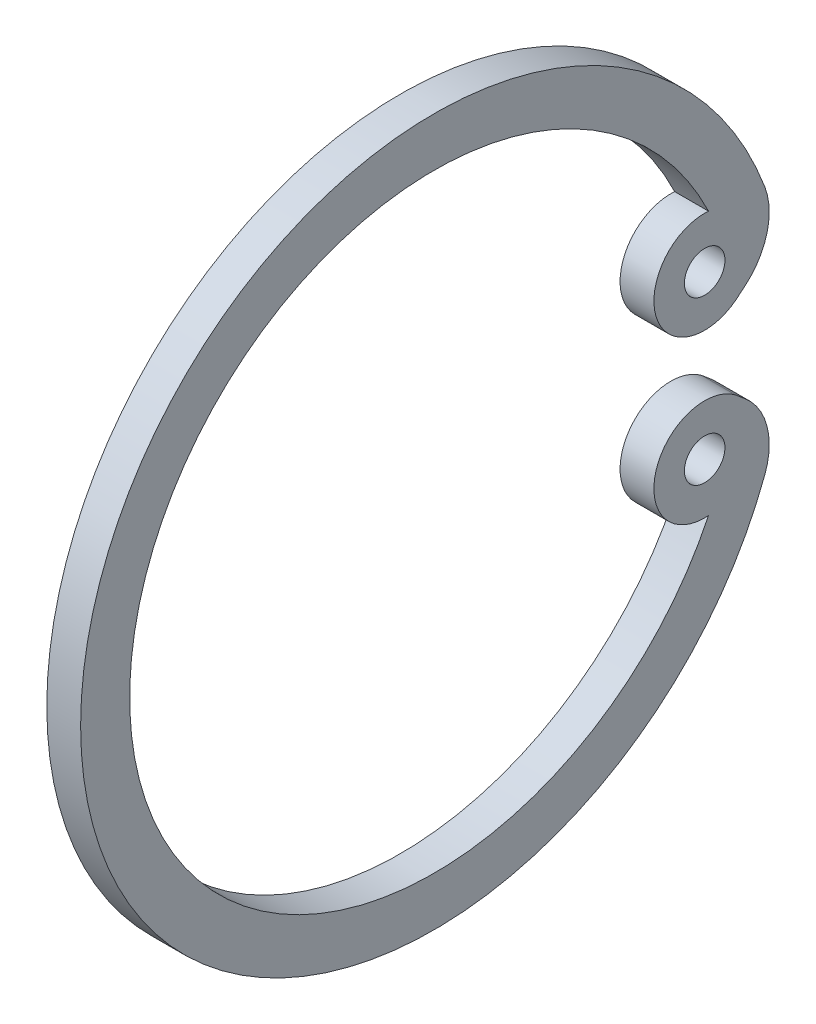
SolidWorks part; units mm, degrees
ref_plane "Front Plane" through (0, 0, 0) normal (0, 0, 1) x (1, 0, 0)
ref_plane "Top Plane" through (0, 0, 0) normal (0, 1, 0) x (1, 0, 0)
ref_plane "Right Plane" through (0, 0, 0) normal (1, 0, 0) x (0, 0, -1)
ref_plane "Plane1" through (19, 0, 0) normal (1, 0, 0) x (0, 0, -1)
sketch "Sketch1" plane through (19, 0, 0) normal (1, 0, 0) x (0, 0, -1)
  line L0 (-1.0829, 1.2142) -> (-0.8063, 1.4448)
  line L1 (-0.8063, -1.4451) -> (-1.0822, -1.2136)
  arc A0 (-1.8869, 3.8965) -> (-1.0829, 1.2142) centre (-2.0005, 2.4008) ccw
  arc A1 (-0.8063, 1.4448) -> (-0.2201, 3.6816) centre (-2.0918, 2.9769) ccw
  arc A2 (-0.2201, 3.6816) -> (-0.2201, -3.6818) centre (-9.9996, -0.0001) ccw
  arc A3 (-0.2201, -3.6818) -> (-0.8063, -1.4451) centre (-2.0918, -2.9772) ccw
  arc A4 (-1.0822, -1.2136) -> (-1.8869, -3.8967) centre (-2.0004, -2.4004) ccw
  arc A5 (-1.8869, -3.8967) -> (-1.8869, 3.8965) centre (-9.9996, -0.0001) cw
  circle A6 centre (-2, -2.4) radius 0.6
  circle A7 centre (-2, 2.4) radius 0.6
extrude "Boss-Extrude1" add sketch "Sketch1" against normal blind 1
scale "Scale1" scale about centroid uniform scaling yes scale factor 0.555556
